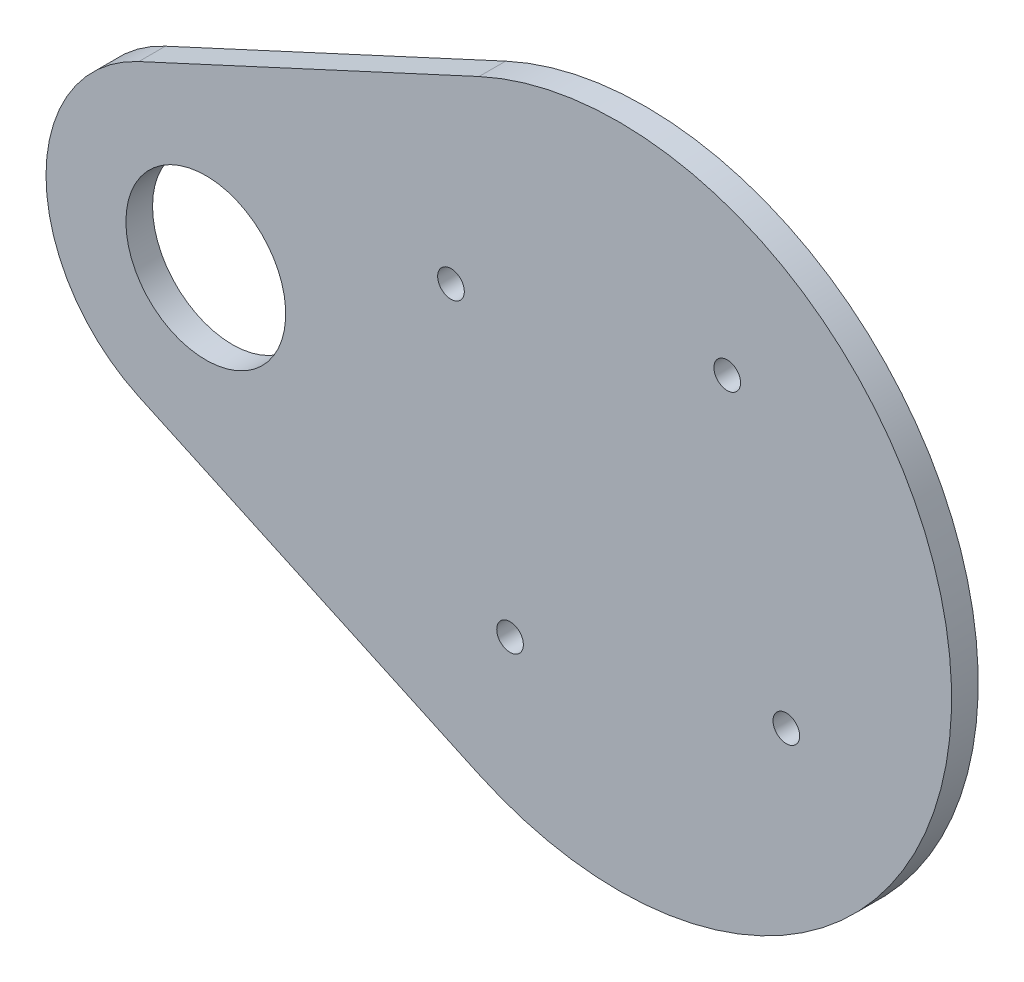
SolidWorks part; units mm, degrees
ref_plane "Front Plane" through (0, 0, 0) normal (0, 0, 1) x (1, 0, 0)
ref_plane "Top Plane" through (0, 0, 0) normal (0, 1, 0) x (1, 0, 0)
ref_plane "Right Plane" through (0, 0, 0) normal (1, 0, 0) x (0, 0, -1)
sketch "Sketch1" plane through (0, 0, 0) normal (0, 0, 1) x (1, 0, 0)
  line L8 (-55.4014, 4.3896) -> (-55.4014, -4.3896)
  line L9 (-46.0323, -10.8939) -> (-36.0323, -10.8939)
  line L10 (-36.0323, -10.8939) -> (-10.4839, -22.6956)
  line L11 (22.5016, -10.8939) -> (32.5016, -10.8939)
  line L12 (41.8707, -4.3896) -> (41.8707, 4.3896)
  line L13 (32.5016, 10.8939) -> (22.5016, 10.8939)
  line L14 (-10.4839, 22.6956) -> (-36.0323, 10.8939)
  line L15 (-36.0323, 10.8939) -> (-46.0323, 10.8939)
  line L18 (-36.0323, -10.8939) -> (-10.4839, -22.6956)
  line L19 (22.5016, -10.8939) -> (32.5016, -10.8939)
  line L22 (-10.4839, 22.6956) -> (-36.0323, 10.8939)
  circle A0 centre (12.59, -8.1543) radius 1 construction
  circle A1 centre (8.1543, 12.59) radius 1 construction
  circle A2 centre (-12.59, 8.1543) radius 1 construction
  circle A3 centre (-8.1543, -12.59) radius 1 construction
  circle A4 centre (12.59, -8.1543) radius 1
  circle A5 centre (8.1543, 12.59) radius 1
  arc A6 (-46.0323, 10.8939) -> (-55.4014, 4.3896) centre (-46.0323, 0.8939) ccw
  arc A7 (-55.4014, -4.3896) -> (-46.0323, -10.8939) centre (-46.0323, -0.8939) ccw
  arc A8 (-10.4839, -22.6956) -> (22.5016, -10.8939) centre (0, 0) ccw
  arc A9 (32.5016, -10.8939) -> (41.8707, -4.3896) centre (32.5016, -0.8939) ccw
  arc A10 (41.8707, 4.3896) -> (32.5016, 10.8939) centre (32.5016, 0.8939) ccw
  arc A11 (22.5016, 10.8939) -> (-10.4839, 22.6956) centre (0, 0) ccw
  arc A14 (-10.4839, -22.6956) -> (22.5016, -10.8939) centre (0, 0) ccw
  arc A17 (22.5016, 10.8939) -> (-10.4839, 22.6956) centre (0, 0) ccw
  circle A18 centre (-12.59, 8.1543) radius 1
  circle A19 centre (-8.1543, -12.59) radius 1
  circle A23 centre (-31, 0) radius 7.5 construction
  circle A24 centre (-31, 0) radius 7.5 construction
  arc A34 (22.5016, 10.8939) -> (22.5016, -10.8939) centre (0, 0) cw
  arc A35 (-36.0323, 10.8939) -> (-36.0323, -10.8939) centre (-31, 0) ccw
  arc A37 (-25.4026, -2.1608) -> (-36.5974, 2.1608) centre (-31, 0) ccw
  arc A38 (-36.5974, 2.1608) -> (-25.4026, -2.1608) centre (-31, 0) ccw
  dimension "D2" = 6
  dimension "D1" = 0
extrude "Boss-Extrude1" add sketch "Sketch1" along normal up to surface (2 mm away)
